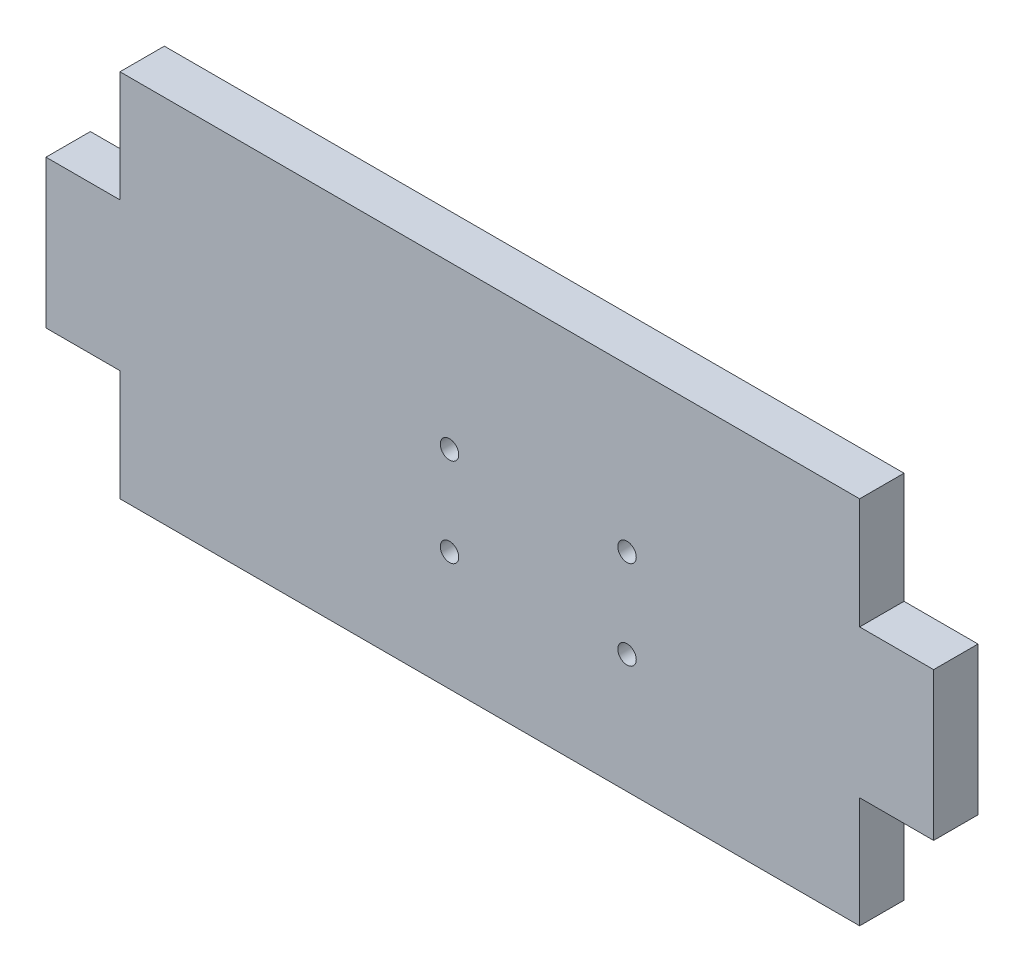
SolidWorks part; units mm, degrees
ref_plane "Plan de face" through (0, 0, 0) normal (0, 0, 1) x (1, 0, 0)
ref_plane "Plan de dessus" through (0, 0, 0) normal (0, 1, 0) x (1, 0, 0)
ref_plane "Plan de droite" through (0, 0, 0) normal (1, 0, 0) x (0, 0, -1)
sketch "Esquisse1" plane through (0, 0, 0) normal (0, 0, 1) x (1, 0, 0)
  line L1 (0, 0) -> (100, 0)
  line L2 (0, 0) -> (0, 50)
  line L3 (0, 50) -> (100, 50)
  line L4 (100, 0) -> (100, 50)
  line L5 (0, 35) -> (-10, 35)
  line L6 (0, 35) -> (0, 15)
  line L7 (0, 15) -> (-10, 15)
  line L8 (-10, 35) -> (-10, 15)
  line L9 (100, 35) -> (110, 35)
  line L10 (100, 35) -> (100, 15)
  line L11 (100, 15) -> (110, 15)
  line L12 (110, 35) -> (110, 15)
  point P13 (-10, 25)
  point P14 (0, 25)
  point P15 (110, 25)
  point P16 (100, 25)
  dimension "D1" = 100
  dimension "D2" = 50
  dimension "D3" = 10
  dimension "D4" = 20
  dimension "D5" = 10
  dimension "D6" = 20
extrude "Boss.-Extru.1" add sketch "Esquisse1" along normal blind 6 contours L5 L8 L7 L2 | L1 L4 L3 L2 | L12 L9 L4 L11
sketch "Esquisse2" plane through (0, 0, 0) normal (0, 0, -1) x (-1, 0, 0)
  circle A0 centre (-44.5503, 16.0653) radius 1.25
  circle A1 centre (-44.5503, 28.0653) radius 1.25
  circle A2 centre (-68.5503, 28.0653) radius 1.25
  circle A3 centre (-68.5503, 16.0653) radius 1.25
  dimension "D1" = 2.5
  dimension "D2" = 2.5
  dimension "D3" = 2.5
  dimension "D4" = 2.5
extrude "Enlèv. mat.-Extru.1" cut sketch "Esquisse2" against normal up to surface (6 mm away) up to face at (50, 25, 6)
sketch "Esquisse3" plane through (0, 0, 0) normal (0, 0, -1) x (-1, 0, 0)
  circle A0 centre (-68.5503, 28.0653) radius 2.5
  circle A1 centre (-44.5503, 28.0653) radius 2.5
  circle A2 centre (-44.5503, 16.0653) radius 2.5
  circle A3 centre (-68.5503, 16.0653) radius 2.5
  dimension "D1" = 5
extrude "Enlèv. mat.-Extru.2" cut sketch "Esquisse3" against normal blind 4
